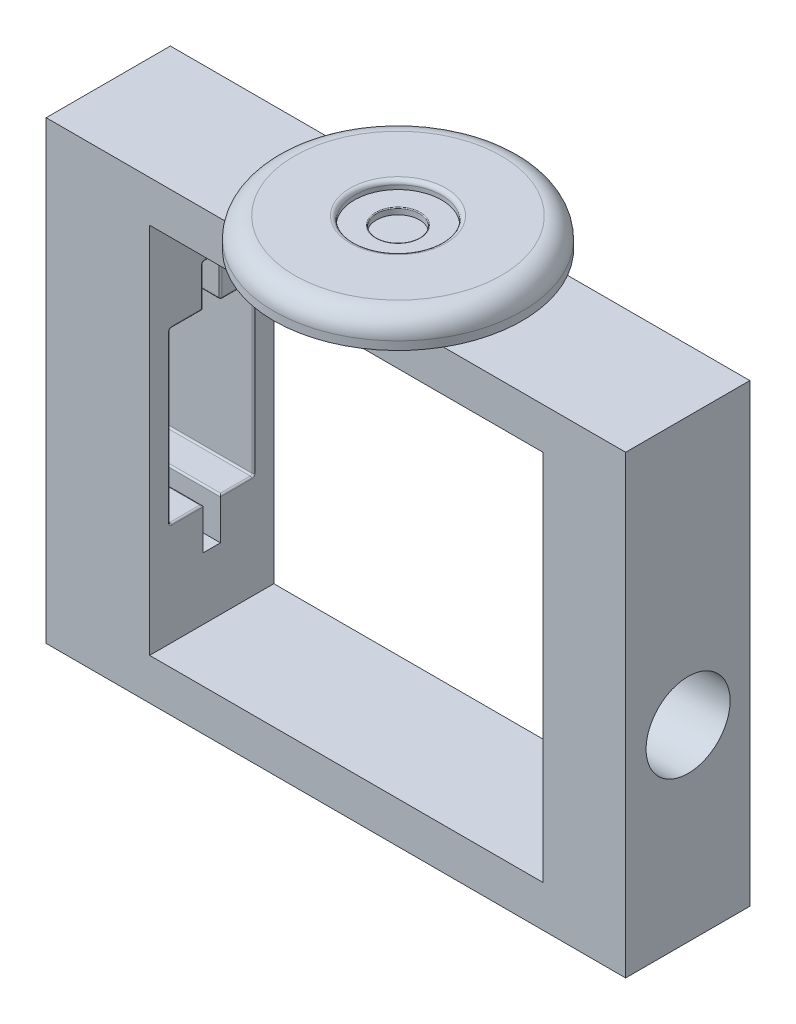
SolidWorks part; units mm, degrees
ref_plane "Front Plane" through (0, 0, 0) normal (0, 0, 1) x (1, 0, 0)
ref_plane "Top Plane" through (0, 0, 0) normal (0, 1, 0) x (1, 0, 0)
ref_plane "Right Plane" through (0, 0, 0) normal (1, 0, 0) x (0, 0, -1)
sketch "Sketch1" plane through (0, 0, 0) normal (1, 0, 0) x (0, 0, -1)
  line L2 (0, 0) -> (-30, 0)
  line L3 (-10.55, 7) -> (-10.55, 5)
  line L4 (-10.55, 5) -> (0, 5)
  line L5 (0, 5) -> (0, 0)
  line L6 (-10.55, 7) -> (-20.1025, 7)
  line L7 (-30, 0) -> (-30, 7)
  line L8 (-30, 7) -> (-20.1025, 7)
  dimension "D3" = 10.55
  dimension "D1" = 2
  dimension "D2" = 5
  dimension "D4" = 30
revolve "Revolve1" add sketch "Sketch1" angle 360 about L5
fillet "Fillet1" radius 1 1 edges at (0, 7, 10.55)
sketch "Sketch2" plane through (0, 5, 0) normal (0, 1, 0) x (1, 0, 0)
  circle A0 centre (0, 0) radius 5.2
  dimension "D1" = 10.4
extrude "Cut-Extrude1" cut sketch "Sketch2" against normal blind 1.5
fillet "Fillet2" radius 0.2 1 edges at (0, 5, 5.2)
fillet "Fillet3" radius 5 1 edges at (0, 7, 30)
ref_plane "Plane1" through (0, 0, 0) normal (0, -1, 0) x (-1, 0, 0)
sketch "Sketch4" plane through (0, 0, 0) normal (0, -1, 0) x (1, 0, 0)
  text T0 "1"
  text T1 "2"
  text T2 "3"
  text T3 "4"
extrude "Cut-Extrude2" cut sketch "Sketch4" against normal blind 1
sketch "Sketch5" plane through (0, 0, 0) normal (0, -1, 0) x (1, 0, 0)
  line L0 (0, -30) -> (0, 30)
  line L1 (-30, 0) -> (30, 0)
  circle A0 centre (0, 0) radius 30 construction
sketch "Sketch14" plane through (0, 0, 0) normal (0, -1, 0) x (1, 0, 0)
  line L0 (0, -30) -> (0, 30) construction
  line L1 (-70, -15) -> (70, -15)
  line L2 (-70, -15) -> (-70, 15)
  line L3 (-70, 15) -> (70, 15)
  line L4 (70, -15) -> (70, 15)
  line L5 (-70, -15) -> (70, 15) construction
  line L6 (-70, 15) -> (70, -15) construction
  point P0 (0, 0)
  dimension "D1" = 140
  dimension "D2" = 30
extrude "Boss-Extrude1" add sketch "Sketch14" along normal blind 10
sketch "Sketch15" plane through (0, -10, 0) normal (0, -1, 0) x (1, 0, 0)
  line L0 (70, 15) -> (-70, 15) construction
  line L1 (-70, -15) -> (-45, -15)
  line L2 (-70, -15) -> (-70, 15)
  line L3 (-70, 15) -> (-45, 15)
  line L4 (-45, -15) -> (-45, 15)
  line L6 (70, -15) -> (50, -15)
  line L7 (70, -15) -> (70, 15)
  line L8 (70, 15) -> (50, 15)
  line L9 (50, -15) -> (50, 15)
  dimension "D1" = 25
  dimension "D2" = 20
extrude "Boss-Extrude2" add sketch "Sketch15" along normal blind 90
sketch "Sketch16" plane through (0, -100, 0) normal (0, -1, 0) x (1, 0, 0)
  line L1 (-70, -15) -> (70, -15)
  line L2 (-70, -15) -> (-70, 15)
  line L3 (-70, 15) -> (70, 15)
  line L4 (70, -15) -> (70, 15)
extrude "Boss-Extrude3" add sketch "Sketch16" along normal blind 10
sketch "Sketch17" plane through (-45, 0, 0) normal (1, 0, 0) x (0, 0, -1)
  line L0 (-15, -110) -> (-15, 0) construction
  line L1 (-10.1, -34.2) -> (10.1, -34.2)
  line L2 (-10.1, -34.2) -> (-10.1, -75)
  line L3 (-10.1, -75) -> (10.1, -75)
  line L4 (10.1, -34.2) -> (10.1, -75)
  line L7 (15, -110) -> (-15, -110) construction
  dimension "D1" = 4.9
  dimension "D2" = 20.2
  dimension "D3" = 40.8
  dimension "D4" = 35
extrude "Cut-Extrude3" cut sketch "Sketch17" against normal blind 25
sketch "Sketch19" plane through (0, -34.2, 0) normal (0, -1, 0) x (1, 0, 0)
  line L0 (-45, 10.1) -> (-45, -10.1) construction
  line L1 (-45, -2.1) -> (-70, -2.1)
  line L2 (-45, -2.1) -> (-45, 2.1)
  line L3 (-45, 2.1) -> (-70, 2.1)
  line L4 (-70, -2.1) -> (-70, 2.1)
  line L5 (-70, 15) -> (-70, -15) construction
  line L6 (-70, -10.1) -> (-45, -10.1) construction
  line L7 (-70, 10.1) -> (-45, 10.1) construction
  dimension "D1" = 8
  dimension "D2" = 8
extrude "Cut-Extrude4" cut sketch "Sketch19" against normal blind 10
sketch "Sketch21" plane through (0, -75, 0) normal (0, 1, 0) x (1, 0, 0)
  line L0 (-45, -10.1) -> (-45, 10.1) construction
  line L1 (-45, 2.1) -> (-70, 2.1)
  line L2 (-45, 2.1) -> (-45, -2.1)
  line L3 (-45, -2.1) -> (-70, -2.1)
  line L4 (-70, 2.1) -> (-70, -2.1)
  line L5 (-70, 10.1) -> (-45, 10.1) construction
  line L6 (-70, -10.1) -> (-45, -10.1) construction
  dimension "D1" = 8
  dimension "D2" = 8
  dimension "D3" = 25
extrude "Cut-Extrude6" cut sketch "Sketch21" against normal blind 10
fillet "Fillet4" radius 0.4 28 edges at (-70, -75, -6.1) (-45, -75, -6.1) (-70, -34.2, -6.1) (-45, -34.2, -6.1) (-70, -24.2, 0) (-45, -24.2, 0) (-70, -34.2, 6.1) (-45, -34.2, 6.1) (-70, -75, 6.1) (-45, -75, 6.1) (-57.5, -75, -10.1) (-70, -54.6, -10.1) (-57.5, -34.2, -10.1) (-45, -54.6, -10.1) (-45, -29.2, 2.1) (-57.5, -24.2, 2.1) (-70, -29.2, 2.1) (-57.5, -34.2, 2.1) (-70, -29.2, -2.1) (-57.5, -24.2, -2.1) (-45, -29.2, -2.1) (-57.5, -34.2, -2.1) (-57.5, -34.2, 10.1) (-70, -54.6, 10.1) (-57.5, -75, 10.1) (-45, -54.6, 10.1) (-57.5, -75, 2.1) (-57.5, -75, -2.1)
sketch "Sketch22" plane through (70, 0, 0) normal (1, 0, 0) x (0, 0, -1)
  circle A0 centre (0.0887, -64.6028) radius 10.15
  dimension "D1" = 20.3
extrude "Cut-Extrude7" cut sketch "Sketch22" against normal blind 22
